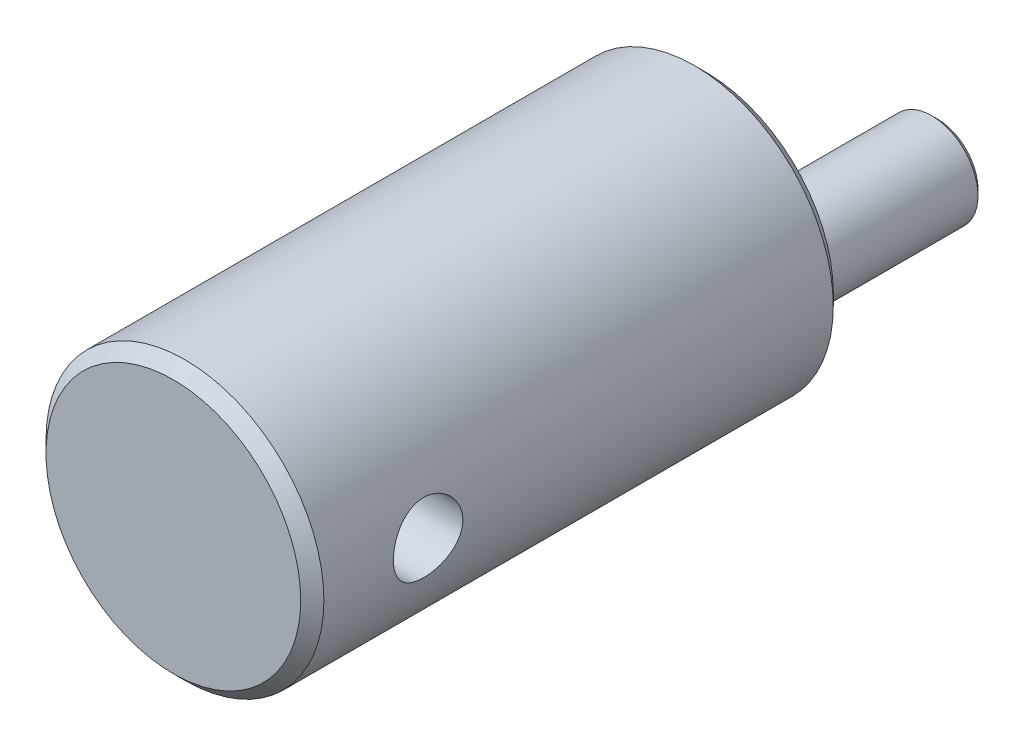
SolidWorks part; units mm, degrees
ref_plane "Front Plane" through (0, 0, 0) normal (0, 0, 1) x (1, 0, 0)
ref_plane "Top Plane" through (0, 0, 0) normal (0, 1, 0) x (1, 0, 0)
ref_plane "Right Plane" through (0, 0, 0) normal (1, 0, 0) x (0, 0, -1)
sketch "Sketch2" plane through (0, 0, 0) normal (0, 0, 1) x (1, 0, 0)
  circle A0 centre (0, 0) radius 6
  dimension "D1" = 12
extrude "Boss-Extrude1" add sketch "Sketch2" along normal blind 23
chamfer "Chamfer1" distance 0.5 angle 45 2 edges at (6, 0, 0) (6, 0, 23)
ref_plane "Plane1" through (-6, 0, 0) normal (1, 0, 0) x (0, 0, -1)
sketch "Sketch3" plane through (-6, 0, 0) normal (1, 0, 0) x (0, 0, -1)
  line L0 (-23, 5.5) -> (-23, -5.5) construction
  circle A0 centre (-18, 0) radius 1.5
  dimension "D2" = 3
  dimension "D1" = 5
extrude "Cut-Extrude1" cut sketch "Sketch3" along normal blind 23
sketch "Sketch5" plane through (0, 0, 0) normal (0, 0, -1) x (-1, 0, 0)
  circle A0 centre (0, -3) radius 2
  dimension "D2" = 4
  dimension "D1" = 3
extrude "Boss-Extrude2" add sketch "Sketch5" along normal blind 10
chamfer "Chamfer2" distance 0.25 angle 45 1 edges at (-2, -3, -10)
